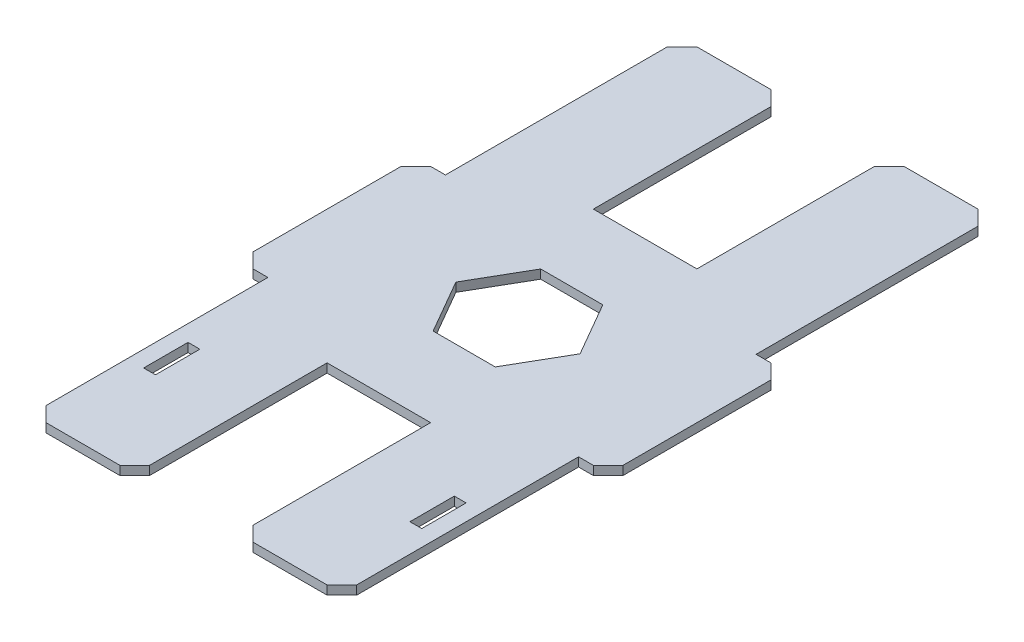
SolidWorks part; units mm, degrees
ref_plane "Front Plane" through (0, 0, 0) normal (0, 0, 1) x (1, 0, 0)
ref_plane "Top Plane" through (0, 0, 0) normal (0, 1, 0) x (1, 0, 0)
ref_plane "Right Plane" through (0, 0, 0) normal (1, 0, 0) x (0, 0, -1)
sketch "Sketch1" plane through (0, 0, 0) normal (0, 1, 0) x (1, 0, 0)
  line L1 (-10, 0) -> (-115, 0)
  line L2 (0, 10) -> (0, 210)
  line L3 (-10, 220) -> (-115, 220)
  line L4 (-125, 10) -> (-125, 210)
  arc A0 (-115, 0) -> (-125, 10) centre (-115, 10) cw
  arc A1 (-10, 0) -> (0, 10) centre (-10, 10) ccw
  arc A2 (0, 210) -> (-10, 220) centre (-10, 210) ccw
  arc A3 (-125, 210) -> (-115, 220) centre (-115, 210) cw
  point P7 (-125, 0)
  point P10 (0, 0)
  point P13 (0, 220)
  dimension "D3" = 10
  dimension "D1" = 220
  dimension "D2" = 125
extrude "Boss-Extrude1" add sketch "Sketch1" along normal blind 3
sketch "Sketch8" plane through (0, 3, 0) normal (0, 1, 0) x (1, 0, 0)
  line L0 (-10, 220) -> (-115, 220) construction
  line L1 (-80, 220) -> (-45, 220)
  line L2 (-80, 220) -> (-80, 155)
  line L3 (-80, 155) -> (-45, 155)
  line L4 (-45, 220) -> (-45, 155)
  line L5 (-125, 110) -> (0, 110) construction
  line L6 (-125, 210) -> (-125, 10) construction
  line L7 (0, 10) -> (0, 210) construction
  line L8 (-80, 0) -> (-45, 0)
  line L9 (-45, 0) -> (-45, 65)
  line L10 (-80, 0) -> (-80, 65)
  line L11 (-80, 65) -> (-45, 65)
  line L12 (-115, 220) -> (-115, 140)
  line L13 (-115, 140) -> (-125, 140)
  line L14 (-10, 220) -> (-10, 140)
  line L15 (-10, 140) -> (0, 140)
  line L16 (-10, 80) -> (0, 80)
  line L17 (-10, 0) -> (-10, 80)
  line L18 (-115, 80) -> (-125, 80)
  line L19 (-115, 0) -> (-115, 80)
  line L20 (-125, 210) -> (-125, 140)
  line L21 (0, 210) -> (0, 140)
  line L22 (0, 80) -> (0, 10)
  line L23 (-125, 80) -> (-125, 10)
  arc A0 (-115, 220) -> (-125, 210) centre (-115, 210) ccw
  arc A1 (-10, 220) -> (0, 210) centre (-10, 210) cw
  arc A2 (-125, 10) -> (-115, 0) centre (-115, 10) ccw
  arc M10 (-125, 10) -> (-115, 0) centre (-115, 10) ccw
  line M11 (-115, 0) -> (-10, 0)
  arc M12 (-10, 0) -> (0, 10) centre (-10, 10) ccw
  line M13 (0, 10) -> (0, 210)
  arc M14 (0, 210) -> (-10, 220) centre (-10, 210) ccw
  line M15 (-10, 220) -> (-115, 220)
  arc M16 (-115, 220) -> (-125, 210) centre (-115, 210) ccw
  line M17 (-125, 210) -> (-125, 10)
  dimension "D1" = 65
  dimension "D2" = 45
  dimension "D3" = 45
  dimension "D4" = 80
  dimension "D5" = 80
extrude "Cut-Extrude4" cut sketch "Sketch8" against normal blind 3 contours L13 L12 M16 M17 | L4 L2 L3 M15 | L14 L15 M13 M14 | L17 L16 M12 M13 | L11 L10 L9 M11 | L19 L18 M10 M17
sketch "Sketch9" plane through (0, 3, 0) normal (0, 1, 0) x (1, 0, 0)
  line L1 (-81.8768, 110.4037) -> (-71.381, 92.2245)
  line L2 (-71.381, 92.2245) -> (-50.3895, 92.2245)
  line L3 (-50.3895, 92.2245) -> (-39.8938, 110.4037)
  line L4 (-39.8938, 110.4037) -> (-50.3895, 128.5828)
  line L5 (-50.3895, 128.5828) -> (-71.381, 128.5828)
  line L6 (-71.381, 128.5828) -> (-81.8768, 110.4037)
  circle A0 centre (-60.8853, 110.4037) radius 18.1792 construction
extrude "Cut-Extrude5" cut sketch "Sketch9" against normal blind 3
sketch "Sketch12" plane through (0, 3, 0) normal (0, 1, 0) x (1, 0, 0)
  line L0 (-110, 220) -> (-115, 215)
  line L1 (-80, 215) -> (-85, 220)
  line L2 (-40, 220) -> (-45, 215)
  line L3 (-10, 215) -> (-15, 220)
  line L4 (-15, 0) -> (-10, 5)
  line L5 (-45, 5) -> (-40, 0)
  line L6 (-85, 0) -> (-80, 5)
  line L7 (-115, 5) -> (-110, 0)
  line L8 (0, 135) -> (-5, 140)
  line L9 (-5, 80) -> (0, 85)
  line L10 (-120, 140) -> (-125, 135)
  line L11 (-125, 85) -> (-120, 80)
  line L12 (-85, 220) -> (-80, 220)
  line L13 (-80, 220) -> (-80, 215)
  line L14 (-110, 220) -> (-115, 220)
  line L15 (-115, 220) -> (-115, 215)
  line L16 (-40, 220) -> (-45, 220)
  line L17 (-45, 220) -> (-45, 215)
  line L18 (-15, 220) -> (-10, 220)
  line L19 (-10, 220) -> (-10, 215)
  line L20 (-10, 5) -> (-10, 0)
  line L21 (-10, 0) -> (-15, 0)
  line L22 (-80, 5) -> (-80, 0)
  line L23 (-80, 0) -> (-85, 0)
  line L24 (-110, 0) -> (-115, 0)
  line L25 (-115, 0) -> (-115, 5)
  line L26 (-120, 140) -> (-125, 140)
  line L27 (-125, 140) -> (-125, 135)
  line L28 (-125, 85) -> (-125, 80)
  line L29 (-125, 80) -> (-120, 80)
  line L30 (-5, 140) -> (0, 140)
  line L31 (0, 140) -> (0, 135)
  line L32 (0, 85) -> (0, 80)
  line L33 (0, 80) -> (-5, 80)
  line L40 (-125, 140) -> (-125, 80)
  line L41 (-125, 80) -> (-115, 80)
  line L42 (-115, 80) -> (-115, 0)
  line L43 (-115, 0) -> (-80, 0)
  line L44 (-80, 0) -> (-80, 65)
  line L45 (-80, 65) -> (-45, 65)
  line L46 (-45, 65) -> (-45, 0)
  line L47 (-45, 0) -> (-10, 0)
  line L48 (-10, 0) -> (-10, 80)
  line L49 (-10, 80) -> (0, 80)
  line L50 (0, 80) -> (0, 140)
  line L51 (0, 140) -> (-10, 140)
  line L52 (-10, 140) -> (-10, 220)
  line L53 (-10, 220) -> (-45, 220)
  line L54 (-45, 220) -> (-45, 155)
  line L55 (-45, 155) -> (-80, 155)
  line L56 (-80, 155) -> (-80, 220)
  line L57 (-80, 220) -> (-115, 220)
  line L58 (-115, 220) -> (-115, 140)
  line L59 (-115, 140) -> (-125, 140)
  line L60 (-125, 135) -> (-125, 85)
  line L68 (-10, 5) -> (-10, 80)
  line L75 (-45, 155) -> (-80, 155)
  line M27 (-125, 140) -> (-125, 80)
  line M29 (-115, 80) -> (-115, 0)
  line M30 (-115, 0) -> (-80, 0)
  line M31 (-80, 0) -> (-80, 65)
  line M33 (-45, 65) -> (-45, 0)
  line M34 (-45, 0) -> (-10, 0)
  line M35 (-10, 0) -> (-10, 80)
  line M36 (-10, 80) -> (0, 80)
  line M37 (0, 80) -> (0, 140)
  line M38 (0, 140) -> (-10, 140)
  line M40 (-10, 220) -> (-45, 220)
  line M41 (-45, 220) -> (-45, 155)
  line M43 (-80, 155) -> (-80, 220)
  line M44 (-80, 220) -> (-115, 220)
  line M45 (-115, 220) -> (-115, 140)
  line M46 (-115, 140) -> (-125, 140)
  dimension "D1" = 0
extrude "Cut-Extrude6" cut sketch "Sketch12" against normal blind 3 contours L2 M40 M41 | L1 M43 M44 | L0 M44 M45 | L8 M37 M38 | L9 M36 M37 | L10 M46 M27 | L7 M29 M30 | L6 M30 M31 | L5 M33 M34 | L4 M34 M35 | L18 L19 L3 | L11 L29 L28
sketch "Sketch14" plane through (0, 0, 0) normal (0, -1, 0) x (1, 0, 0)
  line L0 (-40, 0) -> (-15, 0) construction
  line L1 (-15.5, -47.5) -> (-19.5, -47.5)
  line L2 (-15.5, -47.5) -> (-15.5, -32.5)
  line L3 (-15.5, -32.5) -> (-19.5, -32.5)
  line L4 (-19.5, -47.5) -> (-19.5, -32.5)
  line L5 (-17.5, -32.5) -> (-17.5, -47.5) construction
  line L6 (-15.5, -40) -> (-19.5, -40) construction
  line L7 (-10, -5) -> (-10, -80) construction
  line L11 (-109.5, -40) -> (-105.5, -40) construction
  line L12 (-107.5, -32.5) -> (-107.5, -47.5) construction
  line L13 (-105.5, -47.5) -> (-105.5, -32.5)
  line L14 (-109.5, -32.5) -> (-105.5, -32.5)
  line L15 (-109.5, -47.5) -> (-109.5, -32.5)
  line L16 (-109.5, -47.5) -> (-105.5, -47.5)
  point P0 (-17.5, -40)
  point P22 (-107.5, -40)
  dimension "D1" = 15
  dimension "D2" = 40
  dimension "D3" = 7.5
  dimension "D4" = 4
extrude "Cut-Extrude7" cut sketch "Sketch14" against normal blind 10
